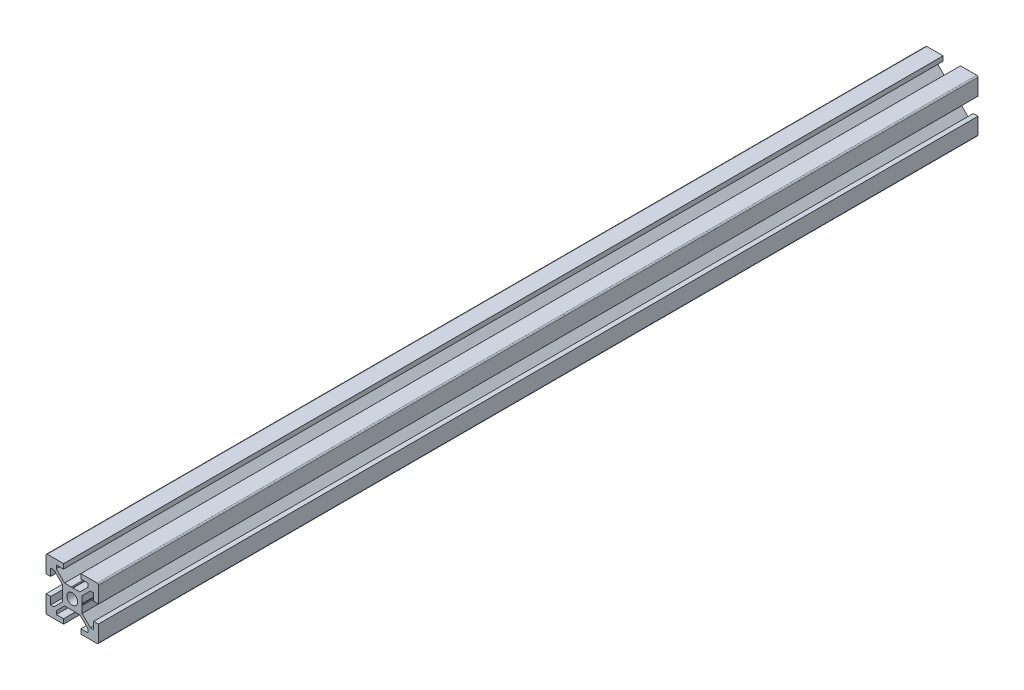
SolidWorks part; units mm, degrees
ref_plane "Front Plane" through (0, 0, 0) normal (0, 0, 1) x (1, 0, 0)
ref_plane "Top Plane" through (0, 0, 0) normal (0, 1, 0) x (1, 0, 0)
ref_plane "Right Plane" through (0, 0, 0) normal (1, 0, 0) x (0, 0, -1)
sketch "Sketch1" plane through (0, 0, 0) normal (0, 0, 1) x (1, 0, 0)
  line L0 (-3.3, 10) -> (-3.3, 8.2)
  line L1 (0, 0) -> (50000, 0) construction
  line L2 (-10, 3.3) -> (-10, 10)
  line L3 (-10, 10) -> (-3.3, 10)
  line L4 (0, 0) -> (0, 50000) construction
  line L5 (-10, -10) -> (10, 10) construction
  line L6 (-10, 10) -> (10, -10) construction
  line L7 (-2.9315, -3.78) -> (-0.34, -3.78)
  line L8 (-3.78, -2.9315) -> (-3.78, -0.34)
  line L9 (-2.9315, 3.78) -> (-0.34, 3.78)
  line L10 (3.78, -2.9315) -> (3.78, -0.34)
  line L11 (-3.78, -3.78) -> (3.78, 3.78) construction
  line L12 (-3.78, 3.78) -> (3.78, -3.78) construction
  line L13 (-6.08, 8.2) -> (-3.3, 8.2)
  line L14 (-8.2, 6.08) -> (-8.2, 3.3)
  line L15 (-8.2, 3.3) -> (-10, 3.3)
  line L16 (-8.2, 6.08) -> (-6.9285, 6.08)
  line L17 (-6.08, 8.2) -> (-6.08, 6.9285)
  line L18 (-6.9285, 6.08) -> (-3.78, 2.9315)
  line L19 (-6.08, 6.9285) -> (-2.9315, 3.78)
  line L20 (8.2, 6.08) -> (6.9285, 6.08)
  line L21 (8.2, 6.08) -> (8.2, 3.3)
  line L22 (8.2, 3.3) -> (10, 3.3)
  line L23 (10, 3.3) -> (10, 10)
  line L24 (10, 10) -> (3.3, 10)
  line L25 (3.3, 10) -> (3.3, 8.2)
  line L26 (6.08, 8.2) -> (3.3, 8.2)
  line L27 (6.08, 8.2) -> (6.08, 6.9285)
  line L28 (6.08, 6.9285) -> (2.9315, 3.78)
  line L29 (6.9285, 6.08) -> (3.78, 2.9315)
  line L30 (6.9285, -6.08) -> (3.78, -2.9315)
  line L31 (6.08, -6.9285) -> (2.9315, -3.78)
  line L32 (6.08, -8.2) -> (6.08, -6.9285)
  line L33 (6.08, -8.2) -> (3.3, -8.2)
  line L34 (3.3, -10) -> (3.3, -8.2)
  line L35 (10, -10) -> (3.3, -10)
  line L36 (10, -3.3) -> (10, -10)
  line L37 (8.2, -3.3) -> (10, -3.3)
  line L38 (8.2, -6.08) -> (8.2, -3.3)
  line L39 (8.2, -6.08) -> (6.9285, -6.08)
  line L40 (-6.08, -6.9285) -> (-2.9315, -3.78)
  line L41 (-6.9285, -6.08) -> (-3.78, -2.9315)
  line L42 (-6.08, -8.2) -> (-6.08, -6.9285)
  line L43 (-8.2, -6.08) -> (-6.9285, -6.08)
  line L44 (-8.2, -3.3) -> (-10, -3.3)
  line L45 (-8.2, -6.08) -> (-8.2, -3.3)
  line L46 (-6.08, -8.2) -> (-3.3, -8.2)
  line L47 (-10, -10) -> (-3.3, -10)
  line L48 (-10, -3.3) -> (-10, -10)
  line L49 (-3.3, -10) -> (-3.3, -8.2)
  line L50 (-0.34, 3.78) -> (0, 3.66)
  line L51 (0.34, 3.78) -> (0, 3.66)
  line L52 (0.34, 3.78) -> (2.9315, 3.78)
  line L53 (-3.78, -0.34) -> (-3.66, 0)
  line L54 (-3.78, 0.34) -> (-3.66, 0)
  line L55 (3.78, 0.34) -> (3.66, 0)
  line L56 (3.78, -0.34) -> (3.66, 0)
  line L57 (-0.34, -3.78) -> (0, -3.66)
  line L58 (0.34, -3.78) -> (0, -3.66)
  line L59 (3.78, 0.34) -> (3.78, 2.9315)
  line L60 (0.34, -3.78) -> (2.9315, -3.78)
  line L61 (-3.78, 0.34) -> (-3.78, 2.9315)
  circle A0 centre (0, 0) radius 2.05
  point P0 (0, 0)
  dimension "D3" = 4.1
  dimension "D1" = 20
  dimension "D2" = 20
  dimension "D4" = 7.56
  dimension "D5" = 6.7
  dimension "D6" = 6.7
  dimension "D7" = 0.6
  dimension "D8" = 3.92
  dimension "D9" = 0.34
  dimension "D10" = 0.12
extrude "Boss-Extrude1" add sketch "Sketch1" along normal blind 157.75
fillet "Fillet1" radius 0.5 4 edges at (-10, 10, 78.875) (-10, -10, 78.875) (10, -10, 78.875) (10, 10, 78.875)
sketch "Sketch2" plane through (0, -10, 0) normal (0, -1, 0) x (1, 0, 0)
  line L0 (0, 0) -> (0, 50000) construction
  line L2 (0, 9) -> (50000, 9) construction
  line L3 (-9.5, 0) -> (-3.3, 0) construction
  circle A0 centre (0, 11.75) radius 2.75
  dimension "D1" = 5.5
  dimension "D2" = 9
extrude "Cut-Extrude1" cut sketch "Sketch2" against normal through all
mirror "Mirror1" about plane through (0, 0, 157.75) normal (0, 0, 1) of "Boss-Extrude1", "Fillet1", "Cut-Extrude1"
sketch "Sketch3" plane through (0, 0, 315.5) normal (0, 0, 1) x (1, 0, 0)
  line L56 (-3.3, 10) -> (-9.5, 10)
  line L57 (-10, 9.5) -> (-10, 3.3)
  line L58 (-10, 3.3) -> (-8.2, 3.3)
  line L59 (-8.2, 3.3) -> (-8.2, 6.08)
  line L60 (-8.2, 6.08) -> (-6.9285, 6.08)
  line L61 (-6.9285, 6.08) -> (-3.78, 2.9315)
  line L62 (-3.78, 2.9315) -> (-3.78, 0.34)
  line L63 (-3.78, 0.34) -> (-3.66, 0)
  line L64 (-3.66, 0) -> (-3.78, -0.34)
  line L65 (-3.78, -0.34) -> (-3.78, -2.9315)
  line L66 (-3.78, -2.9315) -> (-6.9285, -6.08)
  line L67 (-6.9285, -6.08) -> (-8.2, -6.08)
  line L68 (-8.2, -6.08) -> (-8.2, -3.3)
  line L69 (-8.2, -3.3) -> (-10, -3.3)
  line L70 (-10, -3.3) -> (-10, -9.5)
  line L71 (-9.5, -10) -> (-3.3, -10)
  line L72 (-3.3, -10) -> (-3.3, -8.2)
  line L73 (-3.3, -8.2) -> (-6.08, -8.2)
  line L74 (-6.08, -8.2) -> (-6.08, -6.9285)
  line L75 (-6.08, -6.9285) -> (-2.9315, -3.78)
  line L76 (-2.9315, -3.78) -> (-0.34, -3.78)
  line L77 (-0.34, -3.78) -> (0, -3.66)
  line L78 (0, -3.66) -> (0.34, -3.78)
  line L79 (0.34, -3.78) -> (2.9315, -3.78)
  line L80 (2.9315, -3.78) -> (6.08, -6.9285)
  line L81 (6.08, -6.9285) -> (6.08, -8.2)
  line L82 (6.08, -8.2) -> (3.3, -8.2)
  line L83 (3.3, -8.2) -> (3.3, -10)
  line L84 (3.3, -10) -> (9.5, -10)
  line L85 (10, -9.5) -> (10, -3.3)
  line L86 (10, -3.3) -> (8.2, -3.3)
  line L87 (8.2, -3.3) -> (8.2, -6.08)
  line L88 (8.2, -6.08) -> (6.9285, -6.08)
  line L89 (6.9285, -6.08) -> (3.78, -2.9315)
  line L90 (3.78, -2.9315) -> (3.78, -0.34)
  line L91 (3.78, -0.34) -> (3.66, 0)
  line L92 (3.66, 0) -> (3.78, 0.34)
  line L93 (3.78, 0.34) -> (3.78, 2.9315)
  line L94 (3.78, 2.9315) -> (6.9285, 6.08)
  line L95 (6.9285, 6.08) -> (8.2, 6.08)
  line L96 (8.2, 6.08) -> (8.2, 3.3)
  line L97 (8.2, 3.3) -> (10, 3.3)
  line L98 (10, 3.3) -> (10, 9.5)
  line L99 (9.5, 10) -> (3.3, 10)
  line L100 (3.3, 10) -> (3.3, 8.2)
  line L101 (3.3, 8.2) -> (6.08, 8.2)
  line L102 (6.08, 8.2) -> (6.08, 6.9285)
  line L103 (6.08, 6.9285) -> (2.9315, 3.78)
  line L104 (2.9315, 3.78) -> (0.34, 3.78)
  line L105 (0.34, 3.78) -> (0, 3.66)
  line L106 (0, 3.66) -> (-0.34, 3.78)
  line L107 (-0.34, 3.78) -> (-2.9315, 3.78)
  line L108 (-2.9315, 3.78) -> (-6.08, 6.9285)
  line L109 (-6.08, 6.9285) -> (-6.08, 8.2)
  line L110 (-6.08, 8.2) -> (-3.3, 8.2)
  line L111 (-3.3, 8.2) -> (-3.3, 10)
  line L112 (-3.3, 10) -> (-9.5, 10)
  line L113 (-10, 9.5) -> (-10, 3.3)
  line L114 (-10, 3.3) -> (-8.2, 3.3)
  line L115 (-8.2, 3.3) -> (-8.2, 6.08)
  line L116 (-8.2, 6.08) -> (-6.9285, 6.08)
  line L117 (-6.9285, 6.08) -> (-3.78, 2.9315)
  line L118 (-3.78, 2.9315) -> (-3.78, 0.34)
  line L119 (-3.78, 0.34) -> (-3.66, 0)
  line L120 (-3.66, 0) -> (-3.78, -0.34)
  line L121 (-3.78, -0.34) -> (-3.78, -2.9315)
  line L122 (-3.78, -2.9315) -> (-6.9285, -6.08)
  line L123 (-6.9285, -6.08) -> (-8.2, -6.08)
  line L124 (-8.2, -6.08) -> (-8.2, -3.3)
  line L125 (-8.2, -3.3) -> (-10, -3.3)
  line L126 (-10, -3.3) -> (-10, -9.5)
  line L127 (-9.5, -10) -> (-3.3, -10)
  line L128 (-3.3, -10) -> (-3.3, -8.2)
  line L129 (-3.3, -8.2) -> (-6.08, -8.2)
  line L130 (-6.08, -8.2) -> (-6.08, -6.9285)
  line L131 (-6.08, -6.9285) -> (-2.9315, -3.78)
  line L132 (-2.9315, -3.78) -> (-0.34, -3.78)
  line L133 (-0.34, -3.78) -> (0, -3.66)
  line L134 (0, -3.66) -> (0.34, -3.78)
  line L135 (0.34, -3.78) -> (2.9315, -3.78)
  line L136 (2.9315, -3.78) -> (6.08, -6.9285)
  line L137 (6.08, -6.9285) -> (6.08, -8.2)
  line L138 (6.08, -8.2) -> (3.3, -8.2)
  line L139 (3.3, -8.2) -> (3.3, -10)
  line L140 (3.3, -10) -> (9.5, -10)
  line L141 (10, -9.5) -> (10, -3.3)
  line L142 (10, -3.3) -> (8.2, -3.3)
  line L143 (8.2, -3.3) -> (8.2, -6.08)
  line L144 (8.2, -6.08) -> (6.9285, -6.08)
  line L145 (6.9285, -6.08) -> (3.78, -2.9315)
  line L146 (3.78, -2.9315) -> (3.78, -0.34)
  line L147 (3.78, -0.34) -> (3.66, 0)
  line L148 (3.66, 0) -> (3.78, 0.34)
  line L149 (3.78, 0.34) -> (3.78, 2.9315)
  line L150 (3.78, 2.9315) -> (6.9285, 6.08)
  line L151 (6.9285, 6.08) -> (8.2, 6.08)
  line L152 (8.2, 6.08) -> (8.2, 3.3)
  line L153 (8.2, 3.3) -> (10, 3.3)
  line L154 (10, 3.3) -> (10, 9.5)
  line L155 (9.5, 10) -> (3.3, 10)
  line L156 (3.3, 10) -> (3.3, 8.2)
  line L157 (3.3, 8.2) -> (6.08, 8.2)
  line L158 (6.08, 8.2) -> (6.08, 6.9285)
  line L159 (6.08, 6.9285) -> (2.9315, 3.78)
  line L160 (2.9315, 3.78) -> (0.34, 3.78)
  line L161 (0.34, 3.78) -> (0, 3.66)
  line L162 (0, 3.66) -> (-0.34, 3.78)
  line L163 (-0.34, 3.78) -> (-2.9315, 3.78)
  line L164 (-2.9315, 3.78) -> (-6.08, 6.9285)
  line L165 (-6.08, 6.9285) -> (-6.08, 8.2)
  line L166 (-6.08, 8.2) -> (-3.3, 8.2)
  line L167 (-3.3, 8.2) -> (-3.3, 10)
  circle A0 centre (0, 0) radius 2.05 construction
  circle A1 centre (0, 0) radius 2.05
  arc A4 (-9.5, 10) -> (-10, 9.5) centre (-9.5, 9.5) ccw
  arc A5 (-10, -9.5) -> (-9.5, -10) centre (-9.5, -9.5) ccw
  arc A6 (9.5, -10) -> (10, -9.5) centre (9.5, -9.5) ccw
  arc A7 (10, 9.5) -> (9.5, 10) centre (9.5, 9.5) ccw
  arc A8 (-9.5, 10) -> (-10, 9.5) centre (-9.5, 9.5) ccw
  arc A9 (-10, -9.5) -> (-9.5, -10) centre (-9.5, -9.5) ccw
  arc A10 (9.5, -10) -> (10, -9.5) centre (9.5, -9.5) ccw
  arc A11 (10, 9.5) -> (9.5, 10) centre (9.5, 9.5) ccw
  dimension "D1" = 0
extrude "Boss-Extrude2" add sketch "Sketch3" along normal blind 20
